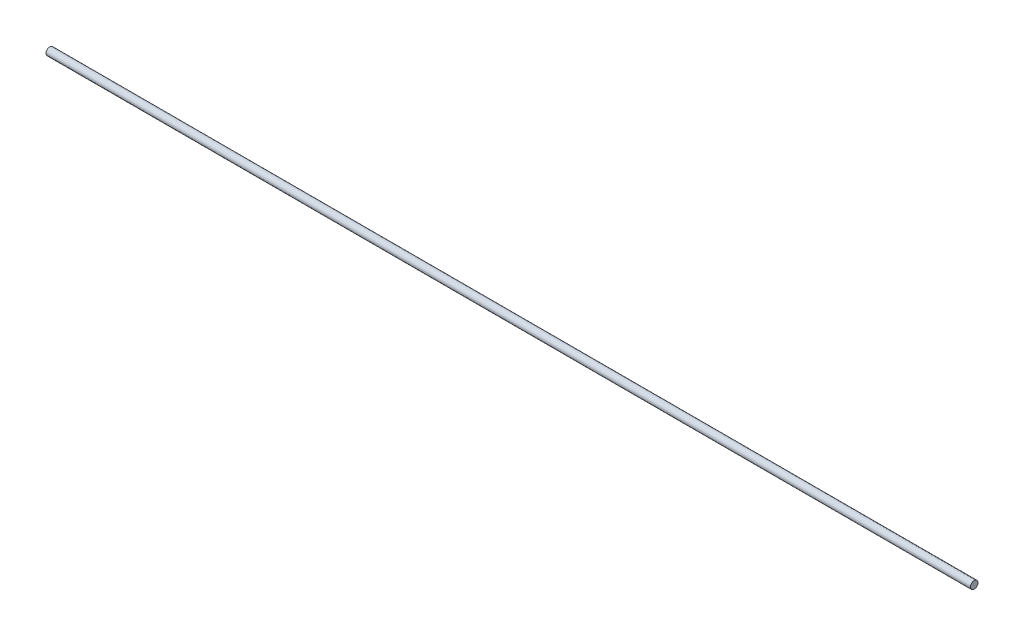
SolidWorks part; units mm, degrees
ref_plane "Front Plane" through (0, 0, 0) normal (0, 0, 1) x (1, 0, 0)
ref_plane "Top Plane" through (0, 0, 0) normal (0, 1, 0) x (1, 0, 0)
ref_plane "Right Plane" through (0, 0, 0) normal (1, 0, 0) x (0, 0, -1)
sketch "Sketch1" plane through (0, 0, 0) normal (1, 0, 0) x (0, 0, -1)
  circle A0 centre (179, 57) radius 1.5
extrude "Boss-Extrude1" add sketch "Sketch1" along normal mid plane 367
